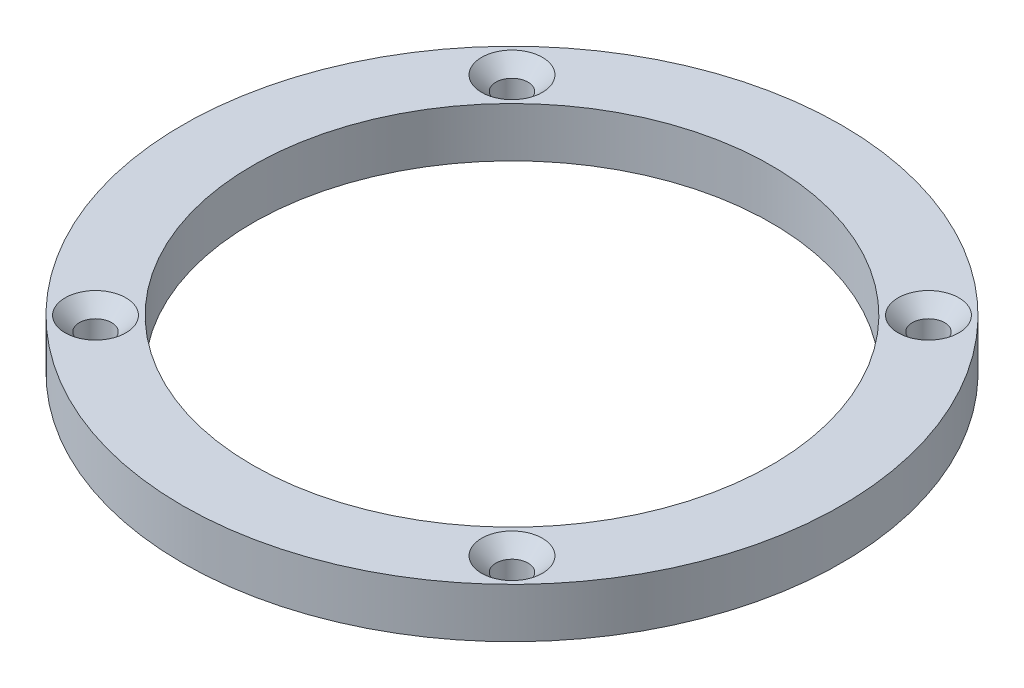
SolidWorks part; units mm, degrees
ref_plane "Front Plane" through (0, 0, 0) normal (0, 0, 1) x (1, 0, 0)
ref_plane "Top Plane" through (0, 0, 0) normal (0, 1, 0) x (1, 0, 0)
ref_plane "Right Plane" through (0, 0, 0) normal (1, 0, 0) x (0, 0, -1)
sketch "Sketch1" plane through (0, 0, 0) normal (0, 1, 0) x (1, 0, 0)
  line L0 (0, 0) -> (43.947, 43.947) construction
  line L1 (0, 0) -> (0, 81.8888) construction
  circle A0 centre (0, 0) radius 44.4
  circle A1 centre (0, 0) radius 56.4
  circle A2 centre (0, 0) radius 50.4 construction
  dimension "D1" = 88.8
  dimension "D4" = 45
  dimension "D2" = 12
  dimension "D3" = 6
extrude "Boss-Extrude1" add sketch "Sketch1" along normal blind 8.5
hole_wizard "CSK for M5 Flat Head Machine Screw1" positions "Sketch4" profile "Sketch5" countersink size "M5" standard "ANSI Metric"
sketch "Sketch4" plane through (0, 8.5, 0) normal (0, 1, 0) x (1, 0, 0)
  line L0 (0, 0) -> (43.947, 43.947) construction
  circle A0 centre (0, 0) radius 50.4 construction
  point P0 (35.6382, 35.6382)
  point P12 (35.6382, -35.6382)
  point P13 (-35.6382, -35.6382)
  point P14 (-35.6382, 35.6382)
  dimension "D1" = 4
sketch "Sketch5" plane through (35.6382, 8.5, -35.6382) normal (1, 0, 0) x (0, 0, 1)
  line L0 (0, 0) -> (0, 31.6524)
  line L1 (0, 31.6524) -> (2.75, 30)
  line L2 (2.75, 30) -> (2.75, 2.45)
  line L3 (2.75, 2.45) -> (5.2, 0)
  line L5 (5.2, 0) -> (0, 0)
  line L6 (-2.75, 2.45) -> (-5.2, 0) construction
  line L10 (0, 31.6524) -> (-2.75, 30) construction
  line L11 (0, -6.35) -> (0, 107.95) construction
  dimension "Hole Dia." = 5.5
  dimension "Hole Depth" = 30
  dimension "Near C'Sink Dia." = 10.4
  dimension "Near C'Sink Angle" = 90
  dimension "Drill Angle" = 118
